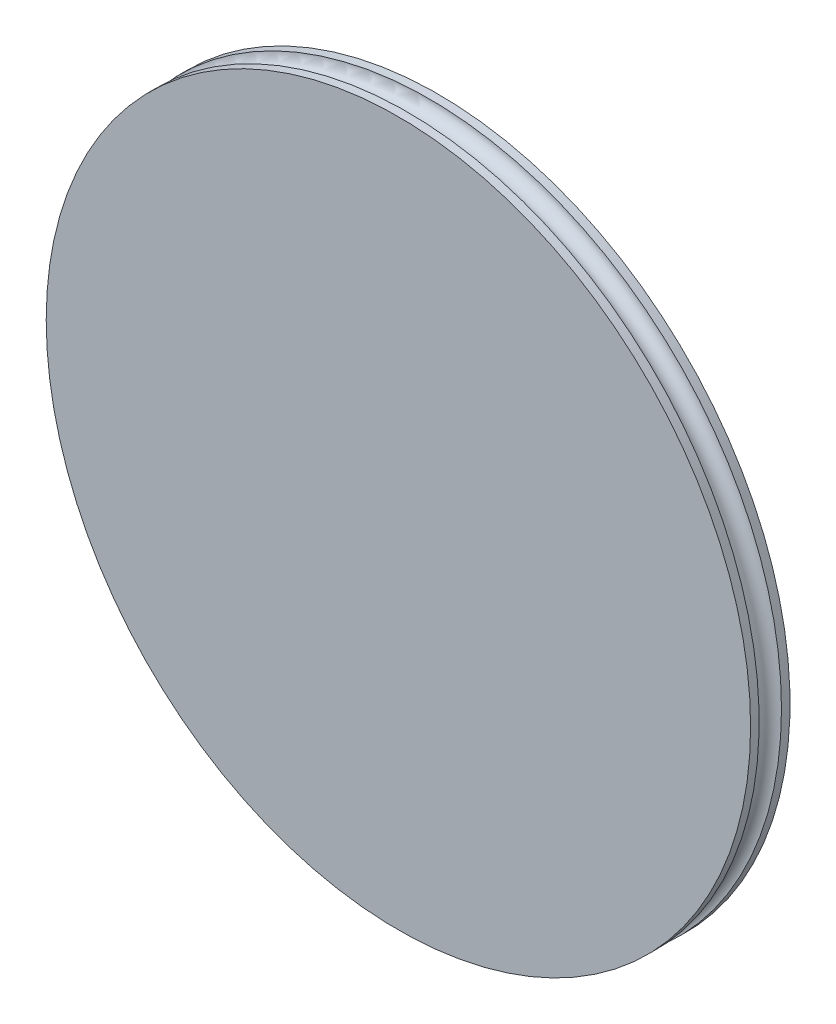
SolidWorks part; units mm, degrees
ref_plane "Спереди" through (0, 0, 0) normal (0, 0, 1) x (1, 0, 0)
ref_plane "Сверху" through (0, 0, 0) normal (0, 1, 0) x (1, 0, 0)
ref_plane "Справа" through (0, 0, 0) normal (1, 0, 0) x (0, 0, -1)
other "Configuration Table"
sketch "Эскиз1" plane through (0, 0, 0) normal (0, 0, 1) x (1, 0, 0)
  line L1 (-2.0022, 2) -> (2.0022, 2)
  line L2 (-2.0022, 2) -> (-2.0022, -2)
  line L3 (-2.0022, -2) -> (2.0022, -2)
  line L4 (2.0022, 2) -> (2.0022, -2)
  line L5 (-2.0022, 2) -> (2.0022, -2) construction
  line L6 (-2.0022, -2) -> (2.0022, 2) construction
  circle A0 centre (0, 0) radius 2.83
  circle A1 centre (0, 0) radius 5.75
  point P0 (0, 0)
  dimension "D2" = 5.66
  dimension "D3" = 11.5
  dimension "D1" = 4
extrude "Бобышка-Вытянуть1" add sketch "Эскиз1" along normal blind 11 contours A1 A0 | L1 A0 | L3 A0
sketch "Эскиз2" plane through (0, 0, 11) normal (0, 0, 1) x (1, 0, 0)
  circle A0 centre (0, 0) radius 26.8
  dimension "D1" = 53.6
extrude "Бобышка-Вытянуть2" add sketch "Эскиз2" along normal blind 1.5 contours A0
sketch "Эскиз3" plane through (0, 0, 11) normal (0, 0, -1) x (-1, 0, 0)
  circle A0 centre (0, 0) radius 24.8
  circle A1 centre (0, 0) radius 26.8
  circle A2 centre (0, 0) radius 26.8 construction
  dimension "D1" = 2
extrude "Бобышка-Вытянуть3" add sketch "Эскиз3" along normal blind 1.5
sketch "Эскиз4" plane through (0, 0, 0) normal (1, 0, 0) x (0, 0, -1)
  line L0 (-11, 26.8) -> (-11, 0)
  line L1 (-9.5, 26.8) -> (-12.5, 26.8) construction
  line L2 (-11, 0) -> (0, 0)
  circle A0 centre (-11, 26.8) radius 0.85
  dimension "D1" = 1.7
revolve "Вырез-Повернуть1" cut sketch "Эскиз4" angle 360 about L2
